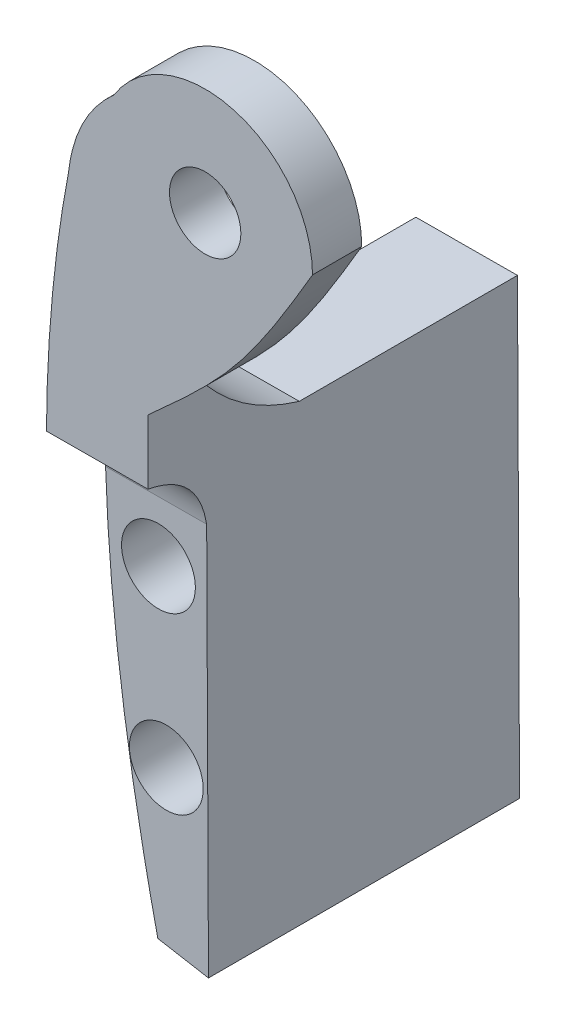
SolidWorks part; units mm, degrees
ref_plane "Front Plane" through (0, 0, 0) normal (0, 0, 1) x (1, 0, 0)
ref_plane "Top Plane" through (0, 0, 0) normal (0, 1, 0) x (1, 0, 0)
ref_plane "Right Plane" through (0, 0, 0) normal (1, 0, 0) x (0, 0, -1)
sketch "Sketch1" plane through (0, 0, 0) normal (0, 0, 1) x (1, 0, 0)
  line L49 (-14.1534, -69.7169) -> (-10.0398, -70.4384)
  line L50 (-10.0398, -70.4384) -> (-10.2316, -28.5481)
  arc A48 (3.1505, -12) -> (-12.9862, -7.4065) centre (-5.5716, -12) ccw
  circle A49 centre (-5.5716, -12) radius 2.9
  spline S2 degree 3 poles (-18.4013, -30.5146) (-18.849, -43.6728) (-17.0302, -56.9394) (-14.1534, -69.7169) knots 0.288119 0.288119 0.288119 0.288119 1 1 1 1
  spline S3 degree 3 poles (-16.6639, -14.6308) (-17.6677, -19.8813) (-18.2201, -25.189) (-18.4013, -30.5146) knots 0 0 0 0 0.288119 0.288119 0.288119 0.288119
  spline S4 degree 2 poles (-16.6639, -14.6308) (-16.1578, -10.2368) (-12.9862, -7.4065) knots 0 0 0 1 1 1
  spline S5 degree 3 poles (3.1505, -12) (1.1214, -15.4485) (-2.5224, -21.6413) (-7.8644, -26.4273) (-10.2316, -28.5481) knots 0 0 0 0 0.556866 1 1 1 1
  dimension "D1" = 5.8
extrude "Boss-Extrude1" add sketch "Sketch1" against normal blind 4
sketch "Sketch2" plane through (0, 0, -4) normal (0, 0, -1) x (-1, 0, 0)
  line L1 (10.2079, -33.7171) -> (18.4664, -33.7549)
  line L6 (10.2316, -28.5481) -> (10.0398, -70.4384)
  line L7 (10.0398, -70.4384) -> (14.1534, -69.7169)
  line L8 (10.2079, -33.7171) -> (10.0398, -70.4384)
  line L9 (10.0398, -70.4384) -> (14.1534, -69.7169)
  arc A1 (12.9862, -7.4065) -> (-3.1505, -12) centre (5.5716, -12) ccw
  parabola Q1 (16.6639, -14.6308) -> (12.9862, -7.4065) focus (10.6183, -12.7527) apex (15.1874, -10.0721)
  spline S3 degree 3 poles (938.4764, 361.2251) (-1091.2534, -828.2679) (1122.0204, 453.267) (-983.2612, -26.7933) knots -8.11143 -8.11143 -8.11143 -8.11143 5.561586 5.561586 5.561586 5.561586 only from (18.4013, -30.5146) to (16.6639, -14.6308)
  spline S4 degree 3 poles (-852.3579, -540.0542) (21.0399, 119.8389) (-73.3283, -80.1542) (129.3516, -34.0846) (-674.0117, -757.7862) knots -6.347213 -6.347213 -6.347213 -6.347213 0.556866 6.878353 6.878353 6.878353 6.878353 only from (-3.1505, -12) to (10.2316, -28.5481)
  spline S5 degree 3 poles (2649.9218, 1356.8113) (-2925.9133, -1861.5437) (3029.4484, 1351.135) (-2902.196, -582.5324) knots -9.750939 -9.750939 -9.750939 -9.750939 9.370969 9.370969 9.370969 9.370969 only from (14.1534, -69.7169) to (18.4013, -30.5146)
  spline S8 degree 3 poles (14.1534, -69.7169) (16.7942, -57.9876) (18.5434, -45.8463) (18.4664, -33.7549) knots 0.288119 0.288119 0.288119 0.288119 0.941598 0.941598 0.941598 0.941598
  dimension "D1" = 0
extrude "Boss-Extrude2" add sketch "Sketch2" along normal blind 26.0124
sketch "Sketch3" plane through (0, 0, 0) normal (0, 0, 1) x (1, 0, 0)
  circle A2 centre (-14.1032, -43.4969) radius 1.75 construction
  circle A4 centre (-13.4668, -57.3465) radius 1.75 construction
  circle A5 centre (-14.1032, -43.4969) radius 1.75
  circle A6 centre (-13.4668, -57.3465) radius 1.75
extrude "Cut-Extrude1" cut sketch "Sketch3" against normal through all
sketch "Sketch4" plane through (-10.3621, -0.0474, 0) normal (1, 0.0046, 0) x (0, 0, -1)
  line L0 (4, -28.501) -> (4, -12.0143) construction
  line L2 (4, -27.8314) -> (2.7366, -37.3905)
  line L3 (2.7366, -37.3905) -> (12.285, -33.67)
  line L4 (30.0124, -33.67) -> (4, -33.67) construction
  spline S0 degree 2 poles (4, -27.8314) (7.1577, -32.1536) (12.285, -33.67) knots 0 0 0 1 1 1
extrude "Boss-Extrude5" add sketch "Sketch4" against normal blind 8.2585
sketch "Sketch5" plane through (-10.3621, -0.0474, 0) normal (1, 0.0046, 0) x (0, 0, -1)
  line L0 (0, -70.3917) -> (0, -28.501) construction
  line L1 (4.7377, -38.5381) -> (4.7377, -70.3917)
  line L2 (30.0124, -70.3917) -> (0, -70.3917) construction
  line L3 (0, -33.7153) -> (0, -70.3917)
  line L4 (0, -70.3917) -> (4.7377, -70.3917)
  spline S0 degree 2 poles (0, -33.7153) (4.0797, -34.4583) (4.7377, -38.5381) knots 0 0 0 1 1 1
extrude "Cut-Extrude2" cut sketch "Sketch5" against normal through all
sketch "Sketch6" plane through (0, 0, -4.7377) normal (0, 0, 1) x (1, 0, 0)
  circle A2 centre (-13.4668, -57.3465) radius 3
  circle A3 centre (-14.1032, -43.4969) radius 3
extrude "Cut-Extrude3" cut sketch "Sketch6" against normal blind 10
